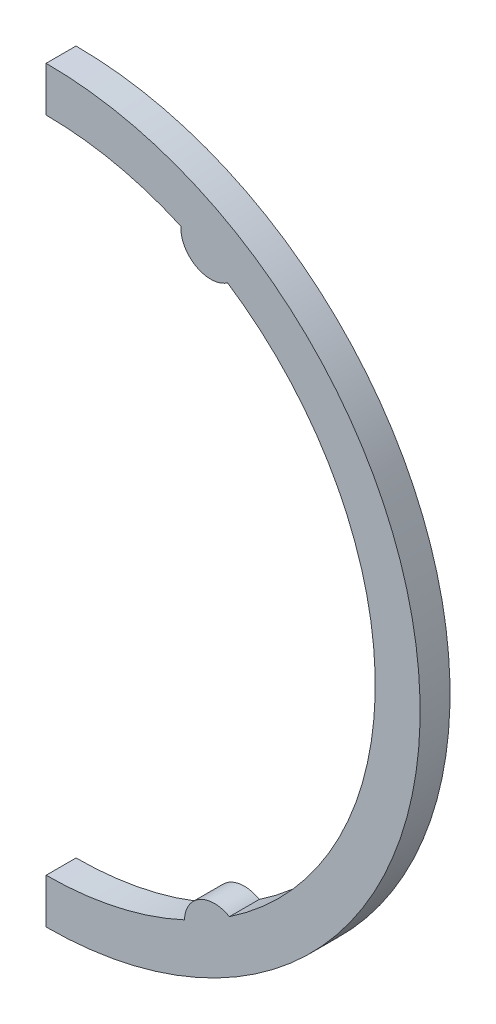
SolidWorks part; units mm, degrees
ref_plane "Alzado" through (0, 0, 0) normal (0, 0, 1) x (1, 0, 0)
ref_plane "Planta" through (0, 0, 0) normal (0, 1, 0) x (1, 0, 0)
ref_plane "Vista lateral" through (0, 0, 0) normal (1, 0, 0) x (0, 0, -1)
sketch "Croquis1" plane through (0, 0, 0) normal (0, 0, 1) x (1, 0, 0)
  line L0 (92.6017, -96.4201) -> (92.6017, -2.1558) construction
  line L1 (50, -100.3854) -> (50, -94.3854)
  line L2 (50, -6.3854) -> (50, -0.3854)
  line L4 (213.2331, -50.3854) -> (-158.3688, -50.3854) construction
  line L5 (100, -50.3854) -> (92.6017, -50.3854) construction
  line L6 (50, -0.3854) -> (100, -0.3854) construction
  line L7 (100, -0.3854) -> (100, -50.3854) construction
  line L8 (100, -50.3854) -> (100, -0.3854) construction
  line L9 (72, -12.2803) -> (72, -100.3854) construction
  arc A0 (50, -0.3854) -> (50, -100.3854) centre (50, -50.3854) cw
  arc A1 (50, -6.3854) -> (68.0028, -10.2369) centre (50, -50.3854) cw
  arc A3 (68.0028, -10.2369) -> (74.266, -13.6816) centre (72, -10.3854) ccw
  arc A6 (68.5009, -90.3068) -> (74.5006, -86.9329) centre (72.4999, -90.3966) cw
  arc A7 (68.5009, -90.3068) -> (50, -94.3854) centre (50, -50.3854) cw
  arc A8 (74.266, -13.6816) -> (74.5006, -86.9329) centre (50, -50.3854) cw
  point P24 (0, 0)
  dimension "D2" = 50
  dimension "D3" = 100
  dimension "D5" = 10
  dimension "D6" = 8
  dimension "D1" = 6
  dimension "D4" = 28
extrude "Saliente-Extruir2" add sketch "Croquis1" along normal blind 4
